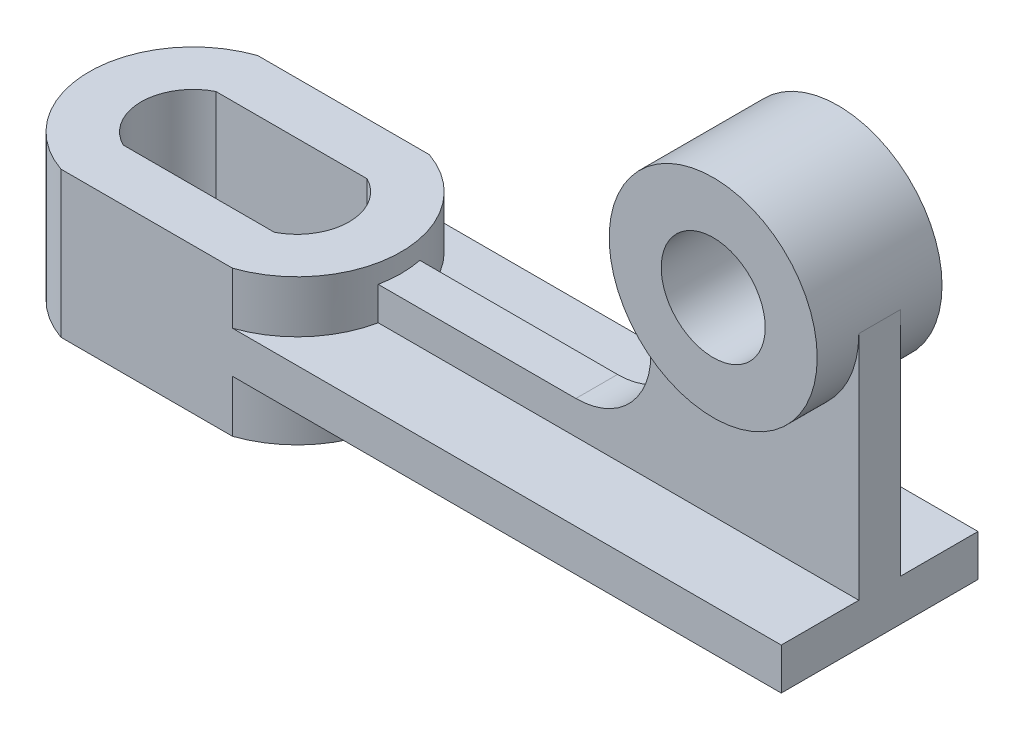
SolidWorks part; units mm, degrees
material "Commercially Pure CP-Ti UNS R50400 (SS)"
ref_plane "Front Plane" through (0, 0, 0) normal (0, 0, 1) x (1, 0, 0)
ref_plane "Top Plane" through (0, 0, 0) normal (0, 1, 0) x (1, 0, 0)
ref_plane "Right Plane" through (0, 0, 0) normal (1, 0, 0) x (0, 0, -1)
sketch "Sketch2" plane through (0, 0, 0) normal (0, 1, 0) x (1, 0, 0)
  line L0 (-37.5, 0) -> (152.5, 0) construction
  line L1 (0, 0) -> (0, -30.9274) construction
  line L3 (-20.627, -23.6422) -> (20.627, -23.6422)
  line L4 (-20.627, 23.6422) -> (20.627, 23.6422)
  line L5 (-18.1659, -11.1422) -> (18.1659, -11.1422)
  line L6 (-18.1659, 11.1422) -> (18.1659, 11.1422)
  arc A2 (-20.627, 23.6422) -> (-20.627, -23.6422) centre (-12.5, 0) ccw
  arc A3 (20.627, 23.6422) -> (20.627, -23.6422) centre (12.5, 0) cw
  arc A4 (-18.1659, 11.1422) -> (-18.1659, -11.1422) centre (-12.5, 0) ccw
  arc A5 (18.1659, 11.1422) -> (18.1659, -11.1422) centre (12.5, 0) cw
  point P7 (-37.5, 0)
  dimension "D4" = 25
  dimension "D1" = 190
  dimension "D2" = 37.5
  dimension "D3" = 25
  dimension "D5" = 12.5
extrude "Boss-Extrude1" add sketch "Sketch2" along normal mid plane 35
sketch "Sketch3" plane through (0, 0, 0) normal (1, 0, 0) x (0, 0, -1)
  line L0 (23.6422, 17.5) -> (23.6422, -17.5) construction
  line L1 (-23.6422, 5) -> (23.6422, 5)
  line L2 (-23.6422, 5) -> (-23.6422, -5)
  line L3 (-23.6422, -5) -> (23.6422, -5)
  line L4 (23.6422, 5) -> (23.6422, -5)
  line L5 (-23.6422, 5) -> (23.6422, -5) construction
  line L6 (-23.6422, -5) -> (23.6422, 5) construction
  point P0 (0, 0)
  dimension "D1" = 10
extrude "Boss-Extrude2" add sketch "Sketch3" along normal blind 152.5
sketch "Sketch4" plane through (0, 17.5, 0) normal (0, 1, 0) x (1, 0, 0)
  line L0 (-18.1659, -11.1422) -> (18.1659, -11.1422) construction
  line L1 (18.1659, 11.1422) -> (-18.1659, 11.1422) construction
  line L6 (-18.1659, -11.1422) -> (18.1659, -11.1422)
  line L7 (18.1659, 11.1422) -> (-18.1659, 11.1422)
  arc A0 (18.1659, -11.1422) -> (18.1659, 11.1422) centre (12.5, 0) ccw construction
  arc A1 (-18.1659, 11.1422) -> (-18.1659, -11.1422) centre (-12.5, 0) ccw construction
  arc A6 (18.1659, -11.1422) -> (18.1659, 11.1422) centre (12.5, 0) ccw
  arc A7 (-18.1659, 11.1422) -> (-18.1659, -11.1422) centre (-12.5, 0) ccw
extrude "Cut-Extrude1" cut sketch "Sketch4" against normal blind 152.5
sketch "Sketch5" plane through (0, 0, 0) normal (0, 0, 1) x (1, 0, 0)
  line L0 (127.5, 5) -> (127.5, 60.5) construction
  line L1 (152.5, 5) -> (20.627, 5) construction
  circle A0 centre (127.5, 60.5) radius 25
  circle A1 centre (127.5, 60.5) radius 12.5
  dimension "D3" = 50
  dimension "D4" = 25
  dimension "D1" = 55.5
  dimension "D2" = 25
extrude "Boss-Extrude3" add sketch "Sketch5" along normal mid plane 30 separate body
sketch "Sketch6" plane through (0, 0, 0) normal (0, 0, 1) x (1, 0, 0)
  line L0 (102.5, 60.5) -> (102.5, 0)
  line L1 (102.5, 0) -> (152.5, 0)
  line L2 (152.5, 0) -> (152.5, 60.5)
  circle A0 centre (127.5, 60.5) radius 25 construction
  arc A1 (102.5, 60.5) -> (152.5, 60.5) centre (127.5, 60.5) ccw
extrude "Boss-Extrude4" add sketch "Sketch6" along normal mid plane 10
sketch "Sketch7" plane through (0, 0, 0) normal (0, 0, 1) x (1, 0, 0)
  line L4 (37.5, 13) -> (102.5, 13)
  line L5 (152.5, 5) -> (20.627, 5) construction
  dimension "D1" = 8
rib "Rib1" sketch "Sketch7" sketch "Sketch7" thickness 10 extrusion direction parallel to sketch draft on no parameters "D1"=10
fillet "Fillet1" radius 18 1 edges at (102.5, 13, 0)
